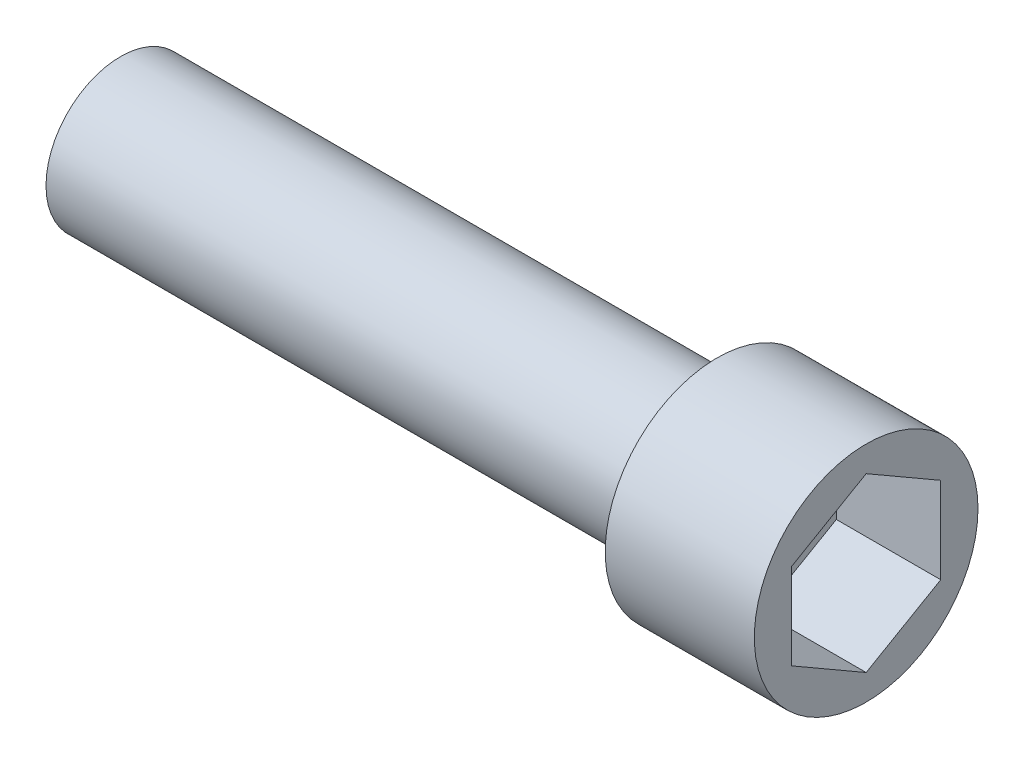
SolidWorks part; units mm, degrees
ref_plane "Front Plane" through (0, 0, 0) normal (1, 0, 0) x (0, 1, 0)
ref_plane "Top Plane" through (0, 0, 0) normal (0, 0, 1) x (0, 1, 0)
ref_plane "Right Plane" through (0, 0, 0) normal (0, 1, 0) x (-1, 0, 0)
sketch "Sketch1" plane through (0, 0, 0) normal (1, 0, 0) x (0, 1, 0)
  circle A0 centre (0, 0) radius 7.5
  dimension "D1" = 15
extrude "Boss-Extrude1" add sketch "Sketch1" along normal blind 10
sketch "Sketch2" plane through (10, 0, 0) normal (1, 0, 0) x (0, 1, 0)
  line L1 (2.8868, -5) -> (5.7735, 0)
  line L2 (5.7735, 0) -> (2.8868, 5)
  line L3 (2.8868, 5) -> (-2.8868, 5)
  line L4 (-2.8868, 5) -> (-5.7735, 0)
  line L5 (-5.7735, 0) -> (-2.8868, -5)
  line L6 (-2.8868, -5) -> (2.8868, -5)
  circle A0 centre (0, 0) radius 5 construction
  dimension "D1" = 10
extrude "Cut-Extrude1" cut sketch "Sketch2" against normal blind 7
sketch "Sketch3" plane through (0, 0, 0) normal (-1, 0, 0) x (0, -1, 0)
  circle A0 centre (0, 0) radius 5
  dimension "D1" = 10
extrude "Boss-Extrude2" add sketch "Sketch3" along normal blind 40
